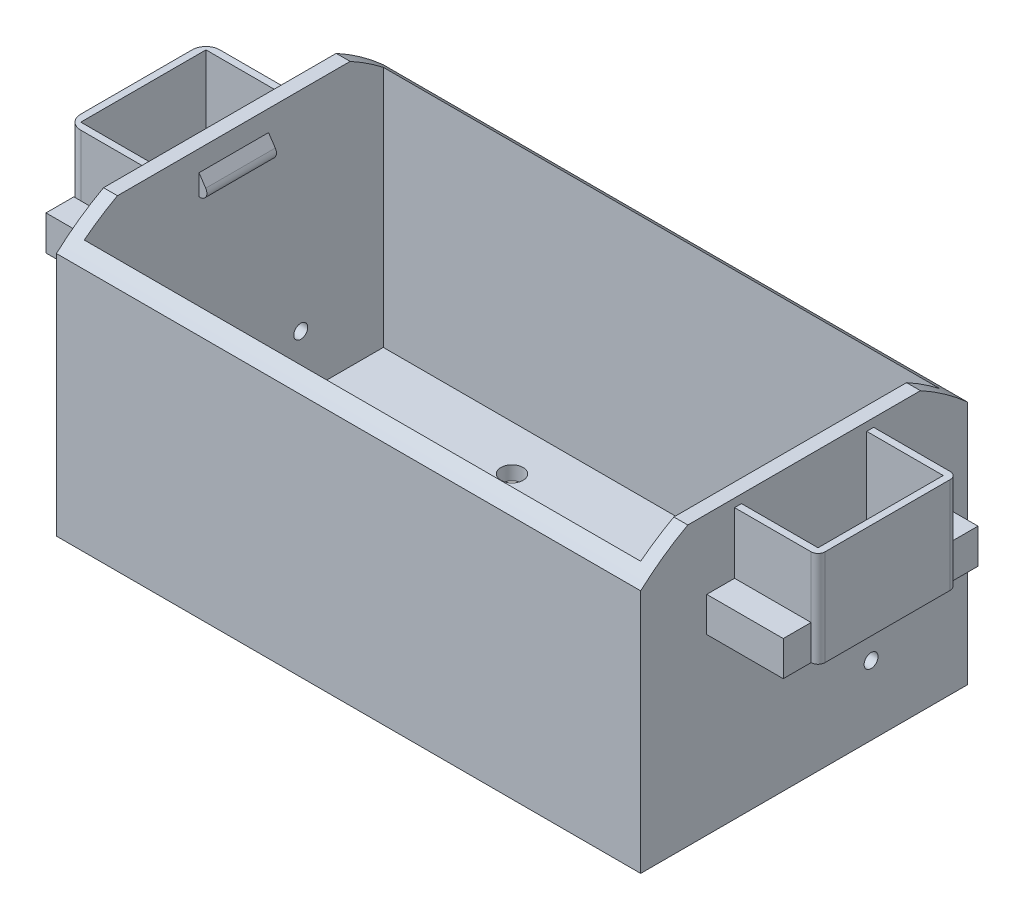
SolidWorks part; units mm, degrees
ref_plane "Front Plane" through (0, 0, 0) normal (0, 0, 1) x (1, 0, 0)
ref_plane "Top Plane" through (0, 0, 0) normal (0, 1, 0) x (1, 0, 0)
ref_plane "Right Plane" through (0, 0, 0) normal (1, 0, 0) x (0, 0, -1)
sketch "Sketch1" plane through (0, 0, 0) normal (0, 1, 0) x (1, 0, 0)
  line L0 (-53.34, 29.845) -> (-53.34, -29.845)
  line L1 (-50.8, 27.305) -> (50.8, 27.305)
  line L2 (-50.8, 27.305) -> (-50.8, -27.305)
  line L3 (-50.8, -27.305) -> (50.8, -27.305)
  line L4 (50.8, 27.305) -> (50.8, -27.305)
  line L5 (-50.8, 27.305) -> (50.8, -27.305) construction
  line L6 (-50.8, -27.305) -> (50.8, 27.305) construction
  line L7 (-53.34, -29.845) -> (53.34, -29.845)
  line L8 (53.34, 29.845) -> (53.34, -29.845)
  line L9 (-53.34, 29.845) -> (53.34, 29.845)
  point P0 (0, 0)
  dimension "D1" = 101.6
  dimension "D2" = 54.61
  dimension "D3" = 2.54
extrude "Boss-Extrude1" add sketch "Sketch1" along normal blind 50.8
sketch "Sketch2" plane through (0, 0, 0) normal (0, -1, 0) x (-1, 0, 0)
  line L6 (-53.34, -29.845) -> (53.34, -29.845)
  line L7 (-53.34, -29.845) -> (-53.34, 29.845)
  line L8 (-53.34, 29.845) -> (53.34, 29.845)
  line L9 (53.34, -29.845) -> (53.34, 29.845)
  line L10 (-53.34, -29.845) -> (53.34, 29.845) construction
  line L11 (-53.34, 29.845) -> (53.34, -29.845) construction
  point P0 (0, 0)
extrude "Boss-Extrude2" add sketch "Sketch2" against normal blind 2.54
sketch "Sketch3" plane through (0, 0, 0) normal (0, -1, 0) x (1, 0, 0)
  line L0 (53.34, 29.845) -> (53.34, -29.845) construction
  circle A1 centre (-19.05, 19.05) radius 2.032
  circle A2 centre (19.05, 19.05) radius 2.032
  circle A3 centre (19.05, -19.05) radius 2.032
  circle A4 centre (-19.05, -19.05) radius 2.032
  dimension "D1" = 19.05
  dimension "D3" = 4.064
  dimension "D7" = 38.1
  dimension "D2" = 19.05
  dimension "D6" = 59.69
  dimension "D8" = 19.05
  dimension "D9" = 19.05
  dimension "D4" = 2
  dimension "D5" = 2
extrude "Cut-Extrude1" cut sketch "Sketch3" against normal blind 2.54
sketch "Sketch5" plane through (0, 0, 0) normal (0, -1, 0) x (1, 0, 0)
  line L0 (0, 0) -> (-68.58, 0) construction
  line L1 (-53.34, -29.845) -> (-53.34, 29.845) construction
  line L3 (-68.58, -12.7) -> (-53.34, -12.7)
  line L4 (-68.58, -12.7) -> (-68.58, 12.7)
  line L5 (-68.58, 12.7) -> (-53.34, 12.7)
  line L6 (-53.34, -12.7) -> (-53.34, 12.7)
  line L7 (-68.58, -12.7) -> (-53.34, 12.7) construction
  line L8 (-68.58, 12.7) -> (-53.34, -12.7) construction
  point P5 (-60.96, 0)
  dimension "D1" = 15.24
  dimension "D2" = 25.4
extrude "Boss-Extrude3" add sketch "Sketch5" against normal blind 17.526 from offset 31.75 offset against normal yes
sketch "Sketch6" plane through (0, 49.276, 0) normal (0, 1, 0) x (1, 0, 0)
  line L0 (-68.58, 12.7) -> (-53.34, 12.7) construction
  line L1 (-67.31, -11.43) -> (-53.34, -11.43)
  line L2 (-67.31, -11.43) -> (-67.31, 11.43)
  line L3 (-67.31, 11.43) -> (-53.34, 11.43)
  line L7 (-53.34, -12.7) -> (-68.58, -12.7) construction
  line L8 (-68.58, -12.7) -> (-68.58, 12.7) construction
  line L9 (-53.34, 11.43) -> (-53.34, -11.43)
  line L10 (-53.34, 12.7) -> (-53.34, -12.7) construction
  dimension "D2" = 1.27
  dimension "D3" = 1.27
  dimension "D4" = 1.27
extrude "Cut-Extrude2" cut sketch "Sketch6" against normal blind 23.114
sketch "Sketch8" plane through (-53.34, -47.0573, -0.7967) normal (-1, 0, 0) x (0, 0, 1)
  circle A0 centre (-11.43, 59.69) radius 1.27
  dimension "D2" = 2.54
extrude "Cut-Extrude3" cut sketch "Sketch8" against normal blind 122.8339
fillet "Fillet3" radius 2.54 2 edges at (-68.58, 40.513, 12.7) (-68.58, 40.513, -12.7)
sketch "Sketch9" plane through (0, 2.54, 0) normal (0, 1, 0) x (1, 0, 0)
  circle A0 centre (0, 0) radius 4.7625
  dimension "D1" = 9.525
extrude "Boss-Extrude4" add sketch "Sketch9" along normal blind 3.175
sketch "Sketch11" plane through (0, 5.715, 0) normal (0, 1, 0) x (1, 0, 0)
  circle A0 centre (0, 0) radius 2.3813
  dimension "D1" = 4.7625
extrude "Cut-Extrude4" cut sketch "Sketch11" against normal through all
sketch "Sketch12" plane through (0, 0, 0) normal (1, 0, 0) x (0, 0, -1)
  line L0 (-29.845, 0) -> (29.845, 0) construction
  line L1 (29.845, 50.8) -> (29.845, 0) construction
  line L3 (-29.845, 50.8) -> (29.845, 50.8) construction
  line L4 (-29.845, 50.8) -> (-29.845, 0) construction
  line L6 (-31.75, 42.8625) -> (31.75, 42.8625)
  line L7 (-31.75, 42.8625) -> (-31.75, 38.1)
  line L8 (-31.75, 38.1) -> (31.75, 38.1)
  line L9 (31.75, 42.8625) -> (31.75, 38.1)
  line L10 (-31.75, 42.8625) -> (31.75, 38.1) construction
  line L11 (-31.75, 38.1) -> (31.75, 42.8625) construction
  line L12 (-31.75, -4.7625) -> (31.75, -4.7625)
  line L13 (-31.75, -4.7625) -> (-31.75, 0)
  line L14 (-31.75, 0) -> (31.75, 0)
  line L15 (31.75, -4.7625) -> (31.75, 0)
  line L16 (-31.75, -4.7625) -> (31.75, 0) construction
  line L17 (-31.75, 0) -> (31.75, -4.7625) construction
  line L18 (29.845, 50.8) -> (29.845, 44.6945)
  line L19 (-29.845, 50.8) -> (-21.2417, 50.8)
  line L20 (-29.845, 50.8) -> (-29.845, 44.6945)
  line L21 (-29.845, 42.8625) -> (-29.845, 38.1)
  line L22 (29.845, 42.8625) -> (29.845, 0)
  line L23 (21.2417, 50.8) -> (29.845, 50.8)
  circle A2 centre (0, 11.754) radius 44.45
  point P6 (0, 40.4813)
  point P18 (0, -2.3813)
  dimension "D1" = 88.9
  dimension "D2" = 63.5
  dimension "D3" = 4.7625
  dimension "D4" = 63.5
  dimension "D5" = 4.7625
  dimension "D6" = 38.1
sketch "Sketch13" plane through (0, 0, 0) normal (0, 0, 1) x (1, 0, 0)
  line L0 (-50.8, 46.99) -> (-48.26, 43.18)
  line L2 (-48.26, 43.18) -> (-50.8, 43.18)
  line L3 (-50.8, 43.18) -> (-50.8, 46.99)
  line L4 (-50.8, 50.8) -> (-50.8, 2.54) construction
  point P2 (0, 0)
  point P5 (0, 0)
  point P6 (0, 0)
  dimension "D1" = 2.54
  dimension "D2" = 3.81
  dimension "D3" = 43.18
extrude "Boss-Extrude5" add sketch "Sketch13" along normal mid plane 12.7
fillet "Fillet4" radius 1.27 1 edges at (-48.26, 43.18, 0)
mirror "Mirror2" about plane through (0, 0, 0) normal (1, 0, 0) of "Fillet4", "Boss-Extrude5"
mirror "Mirror4" about plane through (0, 0, 0) normal (1, 0, 0) of "Cut-Extrude2", "Boss-Extrude3"
fillet "Fillet6" radius 1.27 2 edges at (68.58, 40.513, -12.7) (68.58, 40.513, 12.7)
sketch "Sketch14" plane through (0, 31.75, 0) normal (0, -1, 0) x (1, 0, 0)
  line L0 (-53.34, 12.7) -> (-66.04, 12.7) construction
  line L2 (-67.31, 12.7) -> (-67.31, 17.78)
  line L3 (-67.31, 17.78) -> (-53.34, 17.78)
  line L5 (-53.34, -29.845) -> (-53.34, 29.845) construction
  line L6 (-53.34, 17.78) -> (-53.34, 12.7)
  line L7 (-67.31, 12.7) -> (-53.34, 12.7)
  point P2 (0, 0)
  dimension "D1" = 5.08
  dimension "D2" = 67.31
  dimension "D3" = 5.08
extrude "Boss-Extrude6" add sketch "Sketch14" against normal blind 6.35
mirror "Mirror5" about plane through (0, 0, 0) normal (0, 0, 1) of "Boss-Extrude6"
mirror "Mirror6" about plane through (0, 0, 0) normal (1, 0, 0) of "Boss-Extrude6", "Mirror5"
extrude "Cut-Extrude5" cut sketch "Sketch12" against normal mid plane 254 contours A2 L19 L20 | A2 L18 L23
sketch "Sketch15" plane through (0, 2.54, 0) normal (0, 1, 0) x (1, 0, 0)
  circle A0 centre (-29.21, 0) radius 4.826
  circle A1 centre (29.21, 0) radius 4.826
  dimension "D2" = 9.652
  dimension "D3" = 9.652
  dimension "D1" = 29.21
  dimension "D4" = 29.21
extrude "Boss-Extrude7" add sketch "Sketch15" along normal blind 3.175
